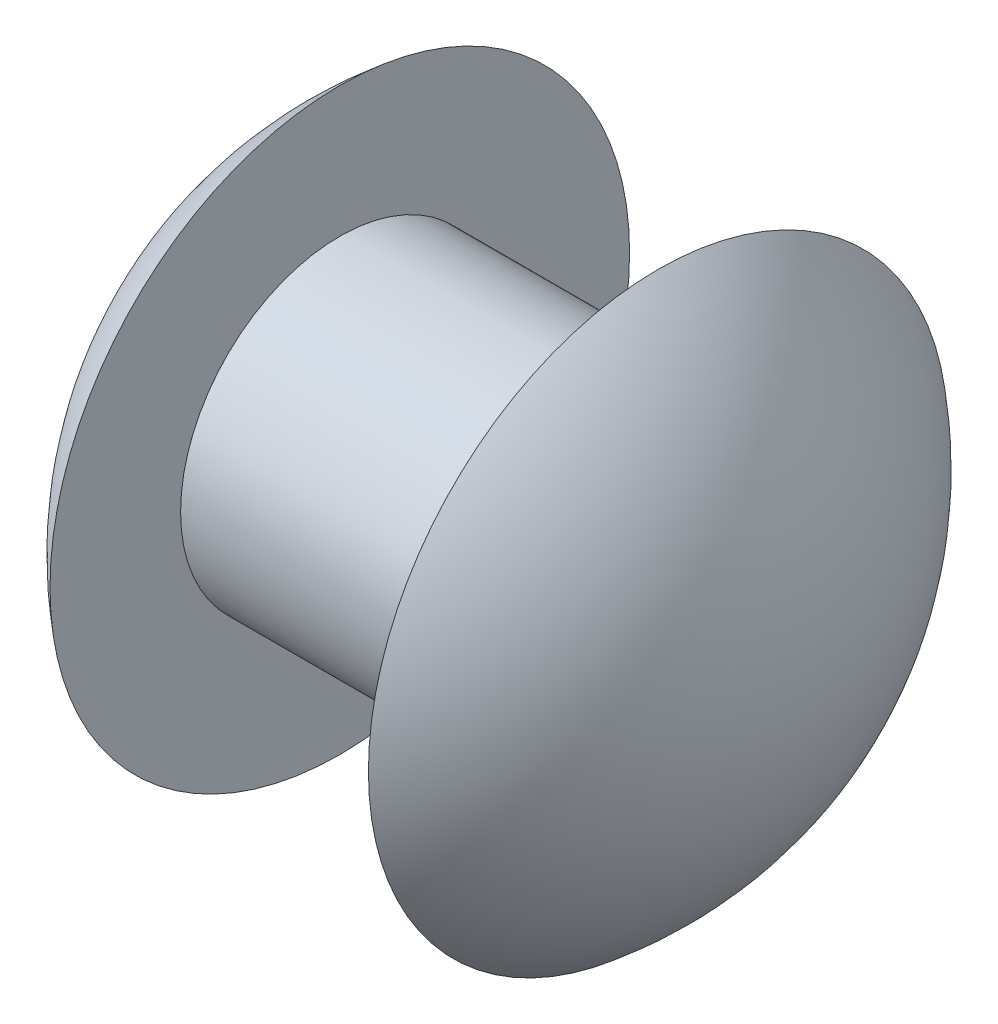
SolidWorks part; units mm, degrees
ref_plane "Спереди" through (0, 0, 0) normal (0, 0, 1) x (1, 0, 0)
ref_plane "Сверху" through (0, 0, 0) normal (0, 1, 0) x (1, 0, 0)
ref_plane "Справа" through (0, 0, 0) normal (1, 0, 0) x (0, 0, -1)
sketch "Эскиз1" plane through (0, 0, 0) normal (0, 0, 1) x (1, 0, 0)
  line L0 (-49.4235, 0) -> (69.1358, 0) construction
  line L1 (-0.0177, 1.5) -> (-0.0177, 2.7303)
  line L2 (-1.3278, 0) -> (4.2924, 0)
  line L3 (2.9823, 1.5) -> (2.9823, 2.7303)
  line L4 (-0.0177, 1.5) -> (2.9823, 1.5)
  arc A0 (-0.0177, 2.7303) -> (-1.3278, 0) centre (2.1722, 0) ccw
  arc A1 (2.9823, 2.7303) -> (4.2924, 0) centre (0.7924, 0) cw
  dimension "D2" = 3.5
  dimension "D1" = 3
  dimension "D3" = 1.5
revolve "Повернуть1" add sketch "Эскиз1" angle 360 about L0
